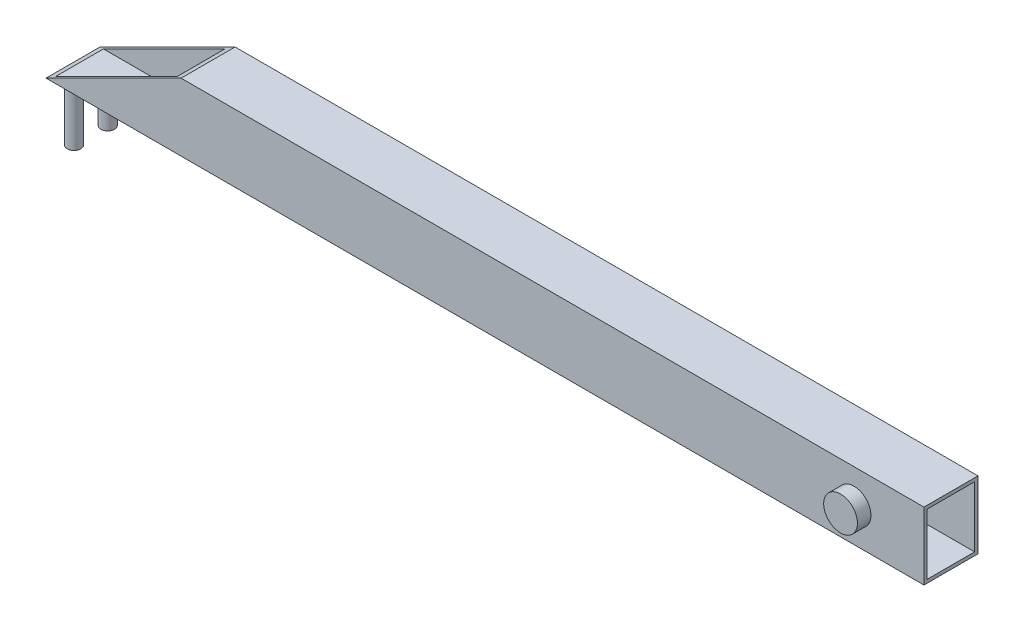
SolidWorks part; units mm, degrees
ref_plane "Plan de face" through (0, 0, 0) normal (0, 0, 1) x (1, 0, 0)
ref_plane "Plan de dessus" through (0, 0, 0) normal (0, 1, 0) x (1, 0, 0)
ref_plane "Plan de droite" through (0, 0, 0) normal (1, 0, 0) x (0, 0, -1)
sketch "Esquisse1" plane through (0, 0, 0) normal (0, 0, 1) x (1, 0, 0)
  line L0 (0, 0) -> (10.3506, 0) construction
  line L1 (0, 0) -> (-27.5207, 0) construction
  line L2 (10.3506, 0) -> (10.3506, 5)
  line L3 (10.3506, 0) -> (10.3506, -5)
  line L4 (10.3506, -5) -> (-119.6494, -5)
  line L5 (10.3506, 5) -> (-99.6494, 5)
  line L6 (-99.6494, 5) -> (-119.6494, -5)
  circle A0 centre (0, 0) radius 2.5
extrude "Boss.-Extru.1" add sketch "Esquisse1" along normal blind 8
sketch "Esquisse2" plane through (10.3506, 0, 0) normal (1, 0, 0) x (0, 0, -1)
  line L2 (0, -5) -> (0, 5) construction
  line L3 (-7.5877, 4.5) -> (-7.5877, -4.5)
  line L4 (-7.5877, 4.5) -> (-0.5, 4.5)
  line L5 (-0.5, 4.5) -> (-0.5, -4.5)
  line L6 (-0.5, -4.5) -> (-7.5877, -4.5)
  line L7 (-8, -5) -> (0, -5) construction
  dimension "D1" = 0.5
  dimension "D2" = 0.5
extrude "Enlèv. mat.-Extru.1" cut sketch "Esquisse2" against normal blind 600
sketch "Esquisse3" plane through (0, 0, 8) normal (0, 0, 1) x (1, 0, 0)
  circle A0 centre (0, 0) radius 2.5
extrude "Boss.-Extru.2" add sketch "Esquisse3" along normal blind 2 separate body
sketch "Esquisse4" plane through (0, -5, 0) normal (0, -1, 0) x (1, 0, 0)
  line L0 (-119.6494, 8) -> (10.3506, 8) construction
  circle A0 centre (-117.0076, 6.5) radius 1
  circle A1 centre (-117.0076, 1.5) radius 1
  dimension "D1" = 5
  dimension "D2" = 1.5
extrude "Boss.-Extru.3" add sketch "Esquisse4" along normal blind 8
